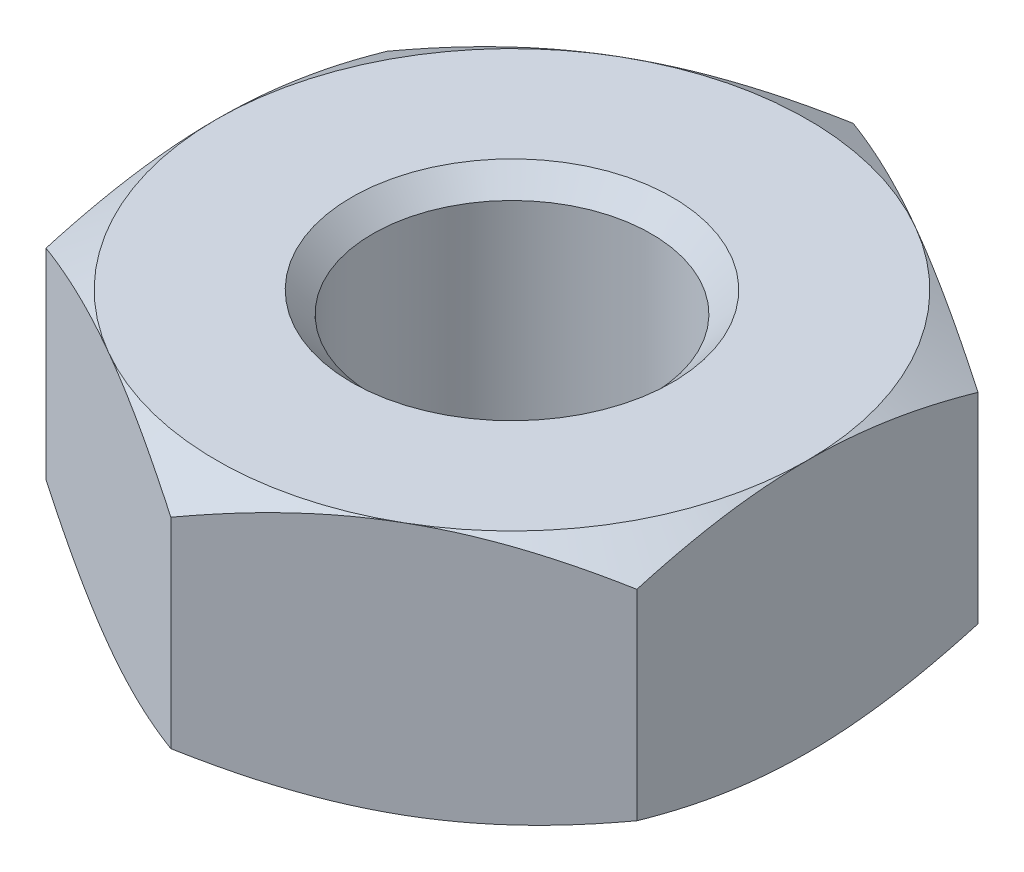
SolidWorks part; units mm, degrees
ref_plane "Front Plane" through (0, 0, 0) normal (0, 0, 1) x (1, 0, 0)
ref_plane "Top Plane" through (0, 0, 0) normal (0, 1, 0) x (1, 0, 0)
ref_plane "Right Plane" through (0, 0, 0) normal (1, 0, 0) x (0, 0, -1)
sketch "Sketch1" plane through (0, 0, 0) normal (0, 1, 0) x (1, 0, 0)
  line L1 (3.5, -2.0207) -> (3.5, 2.0207)
  line L2 (3.5, 2.0207) -> (0, 4.0415)
  line L3 (0, 4.0415) -> (-3.5, 2.0207)
  line L4 (-3.5, 2.0207) -> (-3.5, -2.0207)
  line L5 (-3.5, -2.0207) -> (0, -4.0415)
  line L6 (0, -4.0415) -> (3.5, -2.0207)
  circle A0 centre (0, 0) radius 3.5 construction
  dimension "D1" = 7
extrude "Boss-Extrude1" add sketch "Sketch1" along normal mid plane 3
sketch "Sketch2" plane through (0, 1.5, 0) normal (0, 1, 0) x (1, 0, 0)
  line L0 (3.5, 2.0207) -> (0, 4.0415) construction
  circle A0 centre (0, 0) radius 3.5
extrude "Cut-Extrude1" cut sketch "Sketch2" against normal blind 2.4 draft 60 flip side to cut
mirror "Mirror1" about plane through (0, 0, 0) normal (0, 1, 0) of "Cut-Extrude1"
hole_wizard " Tapped Hole1" positions "Sketch3" profile "Sketch4" tap size "M4" standard "ISO" end condition up to next
sketch "Sketch3" plane through (0, -1.5, 0) normal (0, -1, 0) x (-1, 0, 0)
  point P0 (0, 0)
sketch "Sketch4" plane through (0, -1.5, 0) normal (1, 0, 0) x (0, 0, -1)
  line L0 (0, 0) -> (0, 3)
  line L1 (0, 3) -> (1.65, 3)
  line L2 (1.65, 3) -> (1.65, 0)
  line L5 (1.65, 0) -> (0, 0)
  line L11 (0, -6.35) -> (0, 107.95) construction
  dimension "Thru Tap Drill Dia." = 3.3
  dimension "Thru Tap Drill Depth" = 3
cosmetic thread "Hole Thread1" parameters "D2"=4
chamfer "Chamfer1" distance 0.25 angle 45 2 edges at (0, 1.5, 1.65) (0, -1.5, -1.65)
